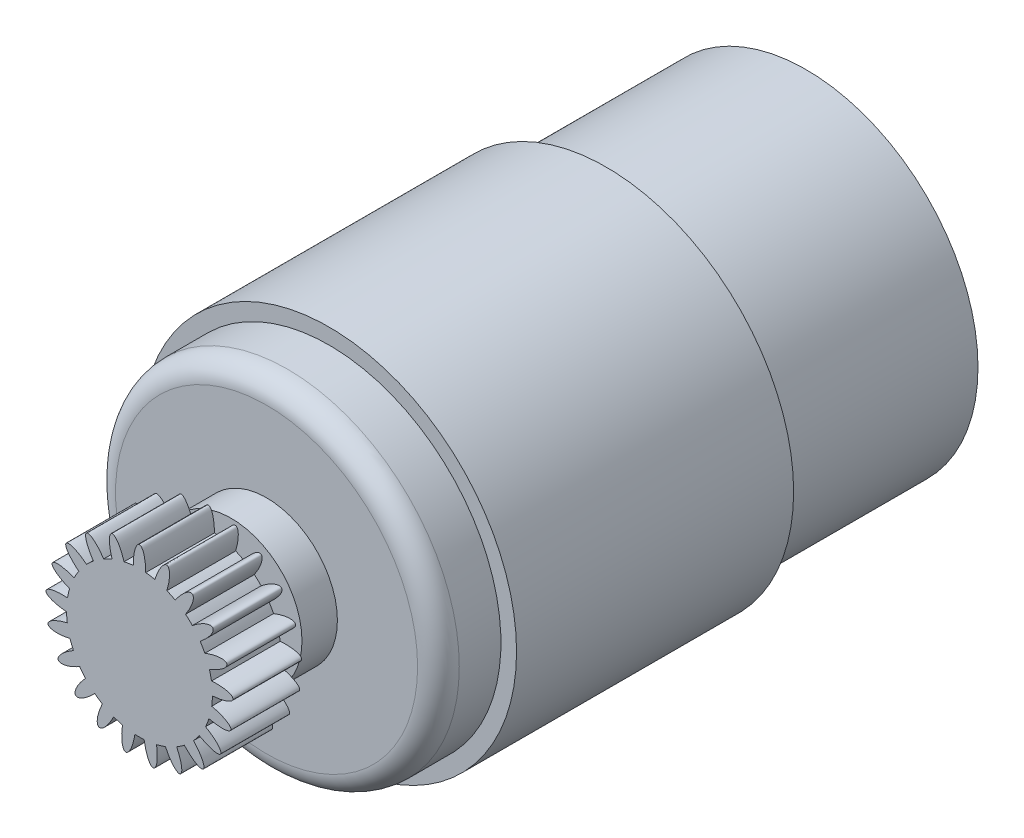
SolidWorks part; units mm, degrees
ref_plane "Front Plane" through (0, 0, 0) normal (0, 0, 1) x (1, 0, 0)
ref_plane "Top Plane" through (0, 0, 0) normal (0, 1, 0) x (1, 0, 0)
ref_plane "Right Plane" through (0, 0, 0) normal (1, 0, 0) x (0, 0, -1)
sketch "Sketch1" plane through (0, 0, 0) normal (0, 0, 1) x (1, 0, 0)
  circle A0 centre (0, 0) radius 22.86
  dimension "D1" = 45.72
extrude "Boss-Extrude1" add sketch "Sketch1" along normal mid plane 33.782
sketch "Sketch2" plane through (0, 0, -16.891) normal (0, 0, -1) x (-1, 0, 0)
  circle A0 centre (0, 0) radius 20.955
  dimension "D1" = 41.91
extrude "Boss-Extrude2" add sketch "Sketch2" along normal blind 24.384
sketch "Sketch3" plane through (0, 0, 16.891) normal (0, 0, 1) x (1, 0, 0)
  circle A0 centre (0, 0) radius 20.955
  dimension "D1" = 41.91
extrude "Boss-Extrude3" add sketch "Sketch3" along normal blind 7.62
sketch "Sketch4" plane through (0, 0, 24.511) normal (0, 0, 1) x (1, 0, 0)
  circle A0 centre (0, 0) radius 8.636
  dimension "D1" = 17.272
extrude "Boss-Extrude4" add sketch "Sketch4" along normal blind 4.318
fillet "Fillet1" radius 2.54 1 edges at (20.955, 0, 24.511)
sketch "Sketch5" plane through (0, 0, 28.829) normal (0, 0, 1) x (1, 0, 0)
  circle A0 centre (0, 0) radius 3.175
  dimension "D1" = 6.35
extrude "Boss-Extrude6" add sketch "Sketch5" along normal offset from surface (11.176 mm away) 15.494 up to face at (18.415, 0, 24.511) offset beyond the face yes
sketch "Sketch6" plane through (0, 0, 40.005) normal (0, 0, 1) x (1, 0, 0)
  circle A0 centre (0, 0) radius 8.89
  dimension "D1" = 17.78
extrude "Boss-Extrude7" add sketch "Sketch6" against normal blind 8.382
ref_axis "Axis1" through (0, 0, 44.069) along (0, 0, -1)
sketch "Sketch7" plane through (0, 0, 40.005) normal (0, 0, 1) x (1, 0, 0)
  line L0 (0, -25.146) -> (0, 25.146) construction
  circle A0 centre (0, 0) radius 8.89 construction
  ellipse E0 centre (0, 8.89) end of major axis (0, 11.43) minor radius 0.762
  dimension "D1" = 2.54
  dimension "D2" = 1.524
extrude "Boss-Extrude8" add sketch "Sketch7" against normal up to surface (8.382 mm away) up to face at (3.175, 0, 31.623)
pattern_circular "CirPattern1" count 21 over 360 about axis through (0, 0, 44.069) along (0, 0, -1) of "Boss-Extrude8"
